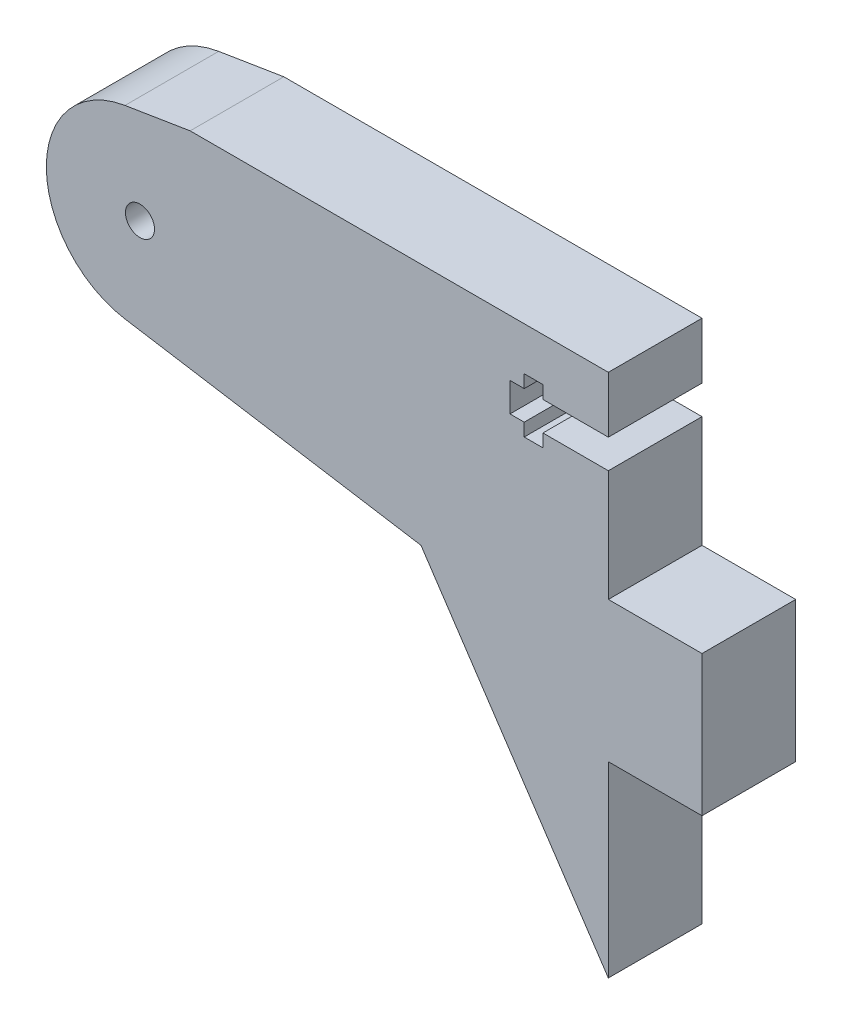
SolidWorks part; units mm, degrees
ref_plane "Płaszczyzna przednia" through (0, 0, 0) normal (0, 0, 1) x (1, 0, 0)
ref_plane "Płaszczyzna górna" through (0, 0, 0) normal (0, 1, 0) x (1, 0, 0)
ref_plane "Płaszczyzna prawa" through (0, 0, 0) normal (1, 0, 0) x (0, 0, -1)
sketch "Szkic1" plane through (0, 0, 0) normal (0, 0, 1) x (1, 0, 0)
  line L0 (-437.0646, -68.9558) -> (-437.0646, -98.9558)
  line L1 (-437.0646, -68.9558) -> (-467.0646, -68.9558)
  line L2 (-447.0646, -128.9558) -> (-467.0646, -98.9558)
  line L4 (-467.0646, -68.9558) -> (-498.6667, -74.0849)
  line L5 (-467.0646, -98.9558) -> (-498.6667, -93.8266)
  line L6 (-447.0646, -128.9558) -> (-437.0646, -128.9558)
  line L7 (-437.0646, -128.9558) -> (-437.0646, -98.9558)
  arc A1 (-498.6667, -74.0849) -> (-498.6667, -93.8266) centre (-497.0646, -83.9558) ccw
  dimension "D3" = 20
  dimension "D1" = 30
  dimension "D2" = 60
  dimension "D4" = 60
  dimension "D5" = 10
extrude "Dodanie-wyciągnięcie1" add sketch "Szkic1" along normal blind 10
sketch "Szkic2" plane through (0, 0, 10) normal (0, 0, 1) x (1, 0, 0)
  circle A0 centre (-497.0646, -83.9558) radius 1.55
  dimension "D1" = 3.1
extrude "Wytnij-wyciągnięcie1" cut sketch "Szkic2" against normal blind 10
sketch "Szkic3" plane through (0, 0, 0) normal (0, 0, -1) x (-1, 0, 0)
  line L0 (437.0646, -108.9558) -> (437.0646, -128.9558)
  line L1 (437.0646, -108.9558) -> (447.0646, -108.9558)
  line L2 (437.0646, -128.9558) -> (447.0646, -128.9558)
  line L3 (447.0646, -108.9558) -> (447.0646, -128.9558)
  line L4 (437.0646, -128.9558) -> (437.0646, -68.9558) construction
  line L6 (437.0646, -68.9558) -> (437.0646, -93.9558)
  line L7 (437.0646, -68.9558) -> (447.0646, -68.9558)
  line L8 (437.0646, -93.9558) -> (447.0646, -93.9558)
  line L9 (447.0646, -68.9558) -> (447.0646, -93.9558)
  dimension "D1" = 20
  dimension "D2" = 10
  dimension "D3" = 10
  dimension "D4" = 15
extrude "Wytnij-wyciągnięcie2" cut sketch "Szkic3" against normal blind 10
sketch "Szkic4" plane through (0, 0, 0) normal (0, 0, -1) x (-1, 0, 0)
  line L0 (447.0646, -78.9558) -> (447.0646, -82.0558)
  line L1 (447.0646, -78.9558) -> (454.0463, -78.9558)
  line L2 (447.0646, -82.0558) -> (454.0463, -82.0558)
  line L3 (457.5646, -78.9558) -> (457.5646, -82.0558)
  line L4 (447.0646, -93.9558) -> (447.0646, -68.9558) construction
  line L5 (454.0463, -82.0558) -> (454.0463, -83.4308)
  line L6 (454.0463, -77.5808) -> (456.0463, -77.5808)
  line L7 (454.0463, -77.5808) -> (454.0463, -78.9558)
  line L8 (454.0463, -83.4308) -> (456.0463, -83.4308)
  line L9 (456.0463, -77.5808) -> (456.0463, -78.9558)
  line L10 (456.0463, -78.9558) -> (457.5646, -78.9558)
  line L11 (456.0463, -82.0558) -> (456.0463, -83.4308)
  line L12 (456.0463, -82.0558) -> (457.5646, -82.0558)
  line L13 (447.0646, -68.9558) -> (467.0646, -68.9558) construction
  dimension "D1" = 10.5
  dimension "D2" = 1.5183
  dimension "D3" = 2
  dimension "D4" = 3.1
  dimension "D5" = 5.85
  dimension "D6" = 1.375
  dimension "D7" = 10
extrude "Wytnij-wyciągnięcie3" cut sketch "Szkic4" against normal blind 10
sketch "Szkic5" plane through (0, 0, 0) normal (0, 0, -1) x (-1, 0, 0)
  line L0 (447.0646, -78.9558) -> (447.0646, -68.9558) construction
  line L1 (447.0646, -68.9558) -> (491.7096, -68.9558)
  line L2 (447.0646, -68.9558) -> (447.0646, -72.9558)
  line L3 (447.0646, -72.9558) -> (491.7096, -72.9558)
  line L4 (491.7096, -68.9558) -> (491.7096, -72.9558)
  line L5 (467.0646, -68.9558) -> (498.6667, -74.0849) construction
  line L6 (447.0646, -68.9558) -> (467.0646, -68.9558) construction
  dimension "D1" = 4
  dimension "D2" = 0
extrude "Wytnij-wyciągnięcie4" cut sketch "Szkic5" against normal blind 10
equation "\"tolerancja_wpusy\"=0.2"
equation "\"dlugosc_wpustu_duzy\"=20"
equation "\"srednica_otworu_M3\"=3.1"
equation "\"szerokosc_nogi_T\"=3.1"
equation "\"dlugosc_T_30\"=11"
equation "\"grubosc_na_nakretke_kwadrat\"=2"
equation "\"szerokosc_na_nakretke_kwadrat\"=5.85"
equation "\"wyokosc_nadstawki_T\"=0.5"
equation "\"dlugosc_T_20_6\"=14"
equation "\"D1@Szkic2\"=\"srednica_otworu_M3\""
equation "\"D3@Szkic4\"=\"grubosc_na_nakretke_kwadrat\""
equation "\"D4@Szkic4\"=\"szerokosc_nogi_T\""
equation "\"D5@Szkic4\"=\"szerokosc_na_nakretke_kwadrat\""
equation "\"D6@Szkic4\"=(\"szerokosc_na_nakretke_kwadrat\"-\"szerokosc_nogi_T\")/2"
